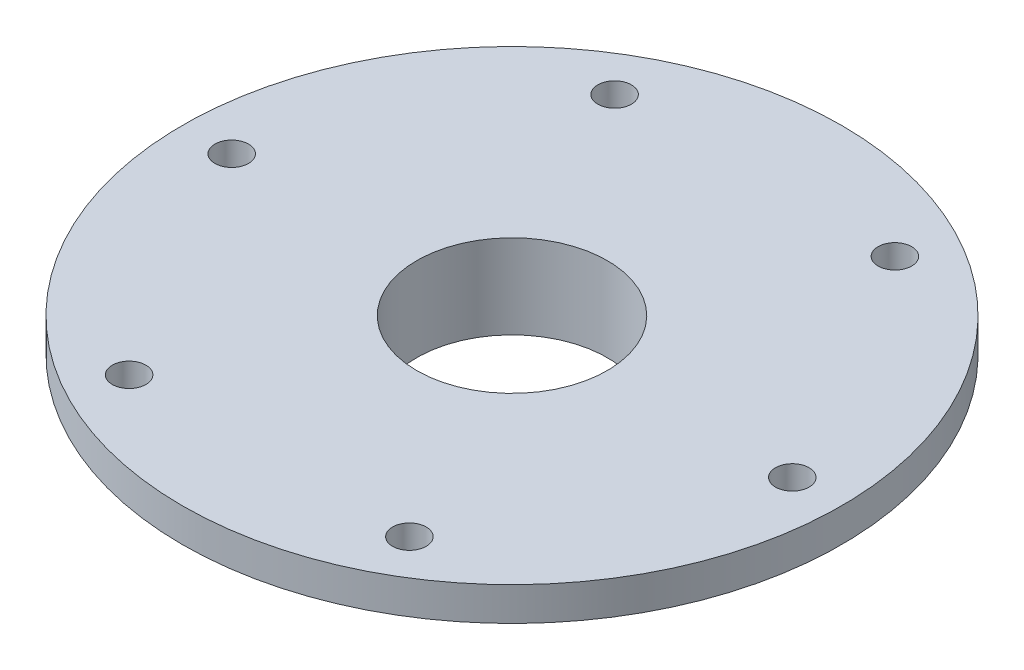
SolidWorks part; units mm, degrees
material "1060 Alloy"
ref_plane "Front Plane" through (0, 0, 0) normal (0, 0, 1) x (1, 0, 0)
ref_plane "Top Plane" through (0, 0, 0) normal (0, 1, 0) x (1, 0, 0)
ref_plane "Right Plane" through (0, 0, 0) normal (1, 0, 0) x (0, 0, -1)
sketch "Sketch4" plane through (0, 0, 0) normal (0, 0, 1) x (1, 0, 0)
  line L0 (0, 27.2792) -> (0, -44.2975) construction
  line L1 (-8.5, 0) -> (-29.3937, 0)
  line L2 (-29.3937, 0) -> (-29.3937, -3)
  line L3 (-29.3937, -3) -> (-11.75, -3)
  line L4 (-11.75, -3) -> (-11.75, -7.5)
  line L5 (-11.75, -7.5) -> (-8.5, -7.5)
  line L6 (-8.5, -7.5) -> (-8.5, 0)
  line L7 (0, 15) -> (-38.0375, 15) construction
  line L8 (0, 20) -> (-12, 20) construction
  line L9 (-12, 20) -> (-38.0375, 15) construction
  line L10 (-25.0188, 17.5) -> (-25.0188, 15) construction
  dimension "D2" = 3
  dimension "D3" = 8.5
  dimension "D4" = 11.75
  dimension "D5" = 4.5
  dimension "D6" = 15
  dimension "D7" = 38.0375
  dimension "D8" = 12
  dimension "D9" = 5
  dimension "D1" = 4.375
revolve "Revolve1" add sketch "Sketch4" angle 360 about L0
sketch "Sketch5" plane through (0, 0, 0) normal (0, 1, 0) x (1, 0, 0)
  line L0 (-12, 0) -> (-38, 0) construction
  circle A0 centre (0, 0) radius 25 construction
  circle A1 centre (-25, 0) radius 1.5
  circle A2 centre (-12.5, 21.6506) radius 1.5
  circle A3 centre (12.5, 21.6506) radius 1.5
  circle A4 centre (25, 0) radius 1.5
  circle A5 centre (12.5, -21.6506) radius 1.5
  circle A6 centre (-12.5, -21.6506) radius 1.5
  circle A7 centre (0, 0) radius 12 construction
  circle A9 centre (0, 0) radius 38 construction
  point P17 (0, 0)
  dimension "D2" = 3
  dimension "D3" = 24
  dimension "D4" = 76
  dimension "D1" = 6
extrude "Cut-Extrude1" cut sketch "Sketch5" against normal through all
equation "\"Stator_OD\"= 60'No Tolerance given"
equation "\"A\"=35.81 'taken off spec sheet for 06808 (A)"
equation "\"Rotor_ID\"= 30'No Tolerance Given"
equation "\"back_bearing_Thickness\"= 5'-0.12"
equation "\"back_bearing_OD\"= 24'-0.009 https://www.mcmaster.com/5972K155/"
equation "\"Stator_Gap\"= 0.0375'+- 0.0125 (From 1.3.3.1 Kollmorgen manual)"
equation "\"Back_mount_hole\"= 1.75'To be tapped to M2 (USE LOCKTITE)"
equation "\"facePlate_Mount_Hole\"= 2.75'To be tapped to M3"
equation "\"final_shaftD\"= 12'To fit in harmonic"
equation "\"final_shaftL\"= 50'random length. Idk"
equation "\"back_bearing_ID\"= 15'"
equation "\"back_bearing_IDOD\"= 16.5'measured off CAD, actually 16.75, but rounded down to nicer number"
equation "\"rotor_shaftD\"= \"Rotor_ID\" - (\"rotor-shaft_gap\")*2'"
equation "\"front_bearing_ID\"= 12'https://www.mcmaster.com/5972K154/"
equation "\"front_bearing_OD\"= 21'-0.009"
equation "\"front_bearing_IDOD\"= 13.5'Measured off CAD. Actually 13.75, but rounded down"
equation "\"front_bearing_Thickness\"= 5'-0.12"
equation "\"rotor_thickness\"= 2.4'measured off CAD"
equation "\"rotor_height\"= 32.86'+-0.075 taken off spec sheet for 06826 (C)"
equation "\"B\"= 26.3'+-0.35 taken off spec sheet for 06826"
equation "\"D3@Sketch4\" = \"back_bearing_ID\" / 2 + 1"
equation "\"D4@Sketch4\"=\"back_bearing_OD\"/2-0.25"
equation "\"D3@Sketch5\"=\"back_bearing_OD\""
equation "\"D4@Sketch5\"=\"Stator_OD\"+16"
equation "\"D7@Sketch4\"=\"Stator_OD\"/2+\"Stator_Gap\"+8"
equation "\"D8@Sketch4\"=\"back_bearing_OD\"/2"
equation "\"D2@Sketch5\"=\"facePlate_Mount_Hole\"+0.25"
equation "\"D1@Sketch4\"=\"facePlate_Mount_Hole\"/2+3"
